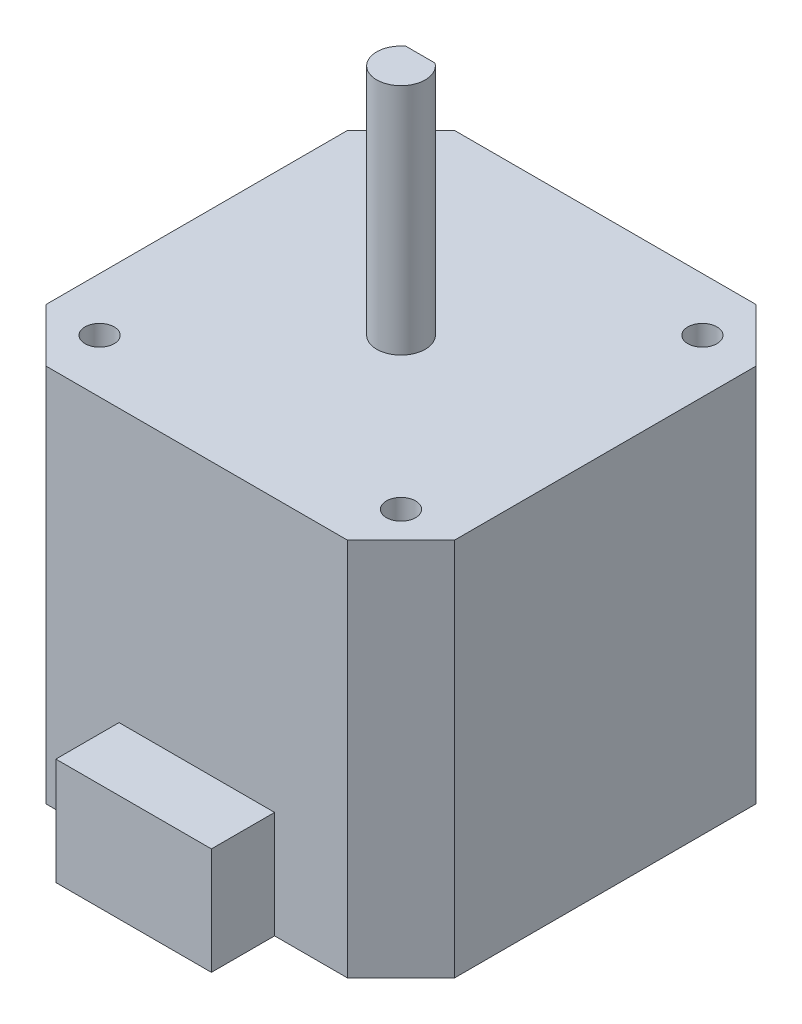
SolidWorks part; units mm, degrees
ref_plane "Front Plane" through (0, 0, 0) normal (0, 0, 1) x (1, 0, 0)
ref_plane "Top Plane" through (0, 0, 0) normal (0, 1, 0) x (1, 0, 0)
ref_plane "Right Plane" through (0, 0, 0) normal (1, 0, 0) x (0, 0, -1)
sketch "Sketch1" plane through (0, 0, 0) normal (0, 1, 0) x (1, 0, 0)
  line L0 (-21, 15.5) -> (-15.5, 21)
  line L1 (15.5, 21) -> (21, 15.5)
  line L2 (-15.5, -21) -> (15.5, -21)
  line L3 (-21, -15.5) -> (-21, 15.5)
  line L4 (-15.5, 21) -> (15.5, 21)
  line L5 (21, -15.5) -> (21, 15.5)
  line L6 (-21, -15.5) -> (-15.5, -21)
  line L7 (15.5, -21) -> (21, -15.5)
  line L8 (-21, 15.5) -> (21, 15.5) construction
  dimension "D1" = 21
  dimension "D2" = 42
  dimension "D3" = 31
  dimension "D4" = 21
  dimension "D5" = 42
  dimension "D6" = 45
extrude "Boss-Extrude1" add sketch "Sketch1" along normal blind 39
sketch "Sketch2" plane through (0, 39, 0) normal (0, 1, 0) x (1, 0, 0)
  circle A0 centre (0, 0) radius 2.5
  dimension "D1" = 5
extrude "Boss-Extrude2" add sketch "Sketch2" along normal blind 9
sketch "Sketch3" plane through (0, 48, 0) normal (0, 1, 0) x (1, 0, 0)
  line L0 (-1.5, 2) -> (1.5, 2)
  line L1 (0, 0) -> (0, -2.5) construction
  arc A0 (-1.5, 2) -> (1.5, 2) centre (0, 0) ccw
  dimension "D2" = 2.5
  dimension "D1" = 4.5
extrude "Boss-Extrude3" add sketch "Sketch3" along normal blind 15
sketch "Sketch4" plane through (0, 39, 0) normal (0, 1, 0) x (1, 0, 0)
  circle A0 centre (-15.5, 15.5) radius 1.5
  circle A1 centre (15.5, 15.5) radius 1.5
  circle A2 centre (15.5, -15.5) radius 1.5
  circle A3 centre (-15.5, -15.5) radius 1.5
  point P8 (0, 0)
  point P10 (0, 0)
  point P12 (0, 0)
  point P13 (0, 0)
  dimension "D1" = 3
extrude "Cut-Extrude1" cut sketch "Sketch4" against normal blind 4.5
sketch "Sketch5" plane through (0, 0, 21) normal (0, 0, 1) x (1, 0, 0)
  line L0 (-15.5, 0) -> (15.5, 0) construction
  line L1 (-8, 0) -> (8, 0)
  line L2 (-8, 0) -> (-8, 11)
  line L3 (-8, 11) -> (8, 11)
  line L4 (8, 0) -> (8, 11)
  dimension "D1" = 11
  dimension "D2" = 16
  dimension "D3" = 8
extrude "Boss-Extrude4" add sketch "Sketch5" along normal blind 6.5
